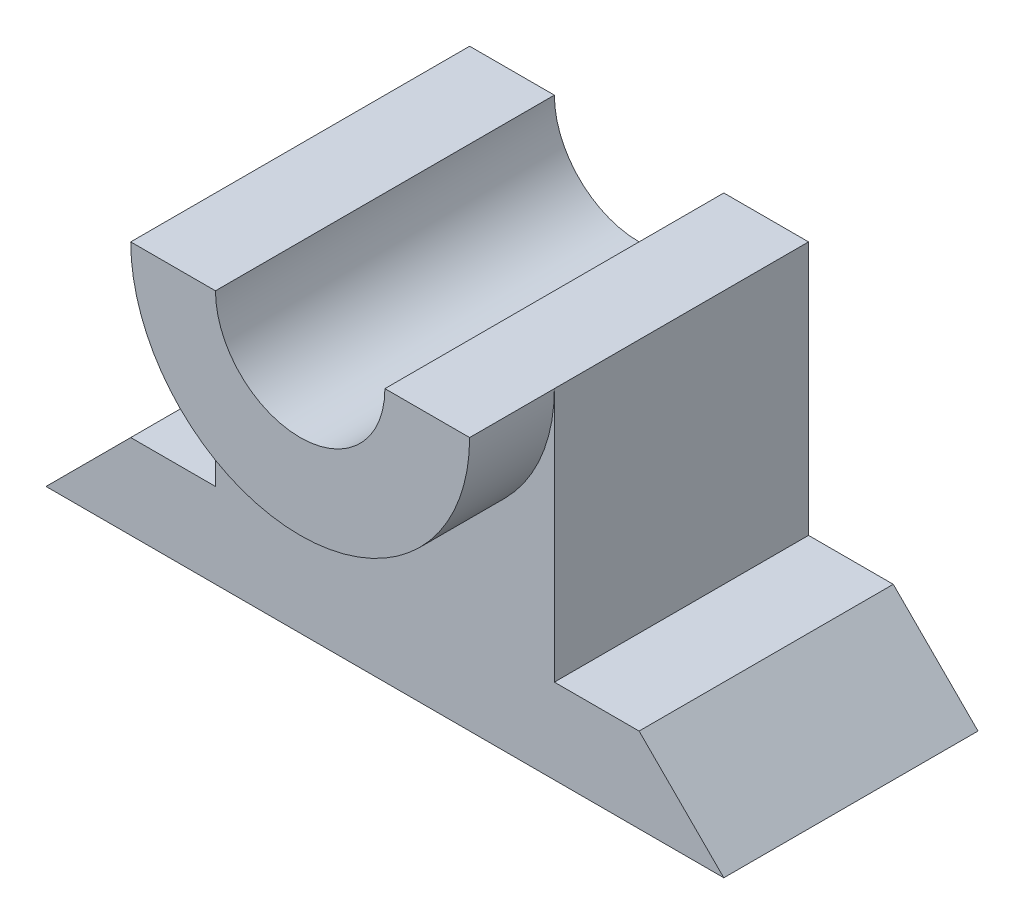
SolidWorks part; units mm, degrees
ref_plane "Front Plane" through (0, 0, 0) normal (0, 0, 1) x (1, 0, 0)
ref_plane "Top Plane" through (0, 0, 0) normal (0, 1, 0) x (1, 0, 0)
ref_plane "Right Plane" through (0, 0, 0) normal (1, 0, 0) x (0, 0, -1)
sketch "Sketch2" plane through (0, 0, 0) normal (0, 0, 1) x (1, 0, 0)
  line L0 (0, 0) -> (80, 0)
  line L1 (10, 10) -> (20, 10)
  line L2 (0, 0) -> (10, 10)
  line L4 (80, 0) -> (70, 10)
  line L7 (20, 10) -> (20, 40)
  line L8 (20, 40) -> (60, 40)
  line L9 (60, 40) -> (60, 10)
  line L10 (60, 10) -> (70, 10)
  dimension "D1" = 80
  dimension "D2" = 45
  dimension "D3" = 45
  dimension "D4" = 10
  dimension "D5" = 10
  dimension "D6" = 40
  dimension "D7" = 40
  dimension "D8" = 10
  dimension "D9" = 10
extrude "Boss-Extrude2" add sketch "Sketch2" against normal blind 30
sketch "Sketch4" plane through (0, 0, 0) normal (0, 0, 1) x (1, 0, 0)
  line L2 (60, 40) -> (20, 40) construction
  line L4 (20, 40) -> (60, 40)
  arc A5 (30, 40) -> (50, 40) centre (40, 40) ccw
  arc A6 (20, 40) -> (60, 40) centre (40, 40) ccw
extrude "Boss-Extrude9" add sketch "Sketch4" along normal blind 10 contours A6 L4
sketch "Sketch12" plane through (0, 0, 10) normal (0, 0, 1) x (1, 0, 0)
  line L0 (20, 40) -> (60, 40) construction
  circle A0 centre (40, 40) radius 10
  point P4 (40, 40)
  point P5 (40, 40)
extrude "Cut-Extrude8" cut sketch "Sketch12" against normal blind 40
